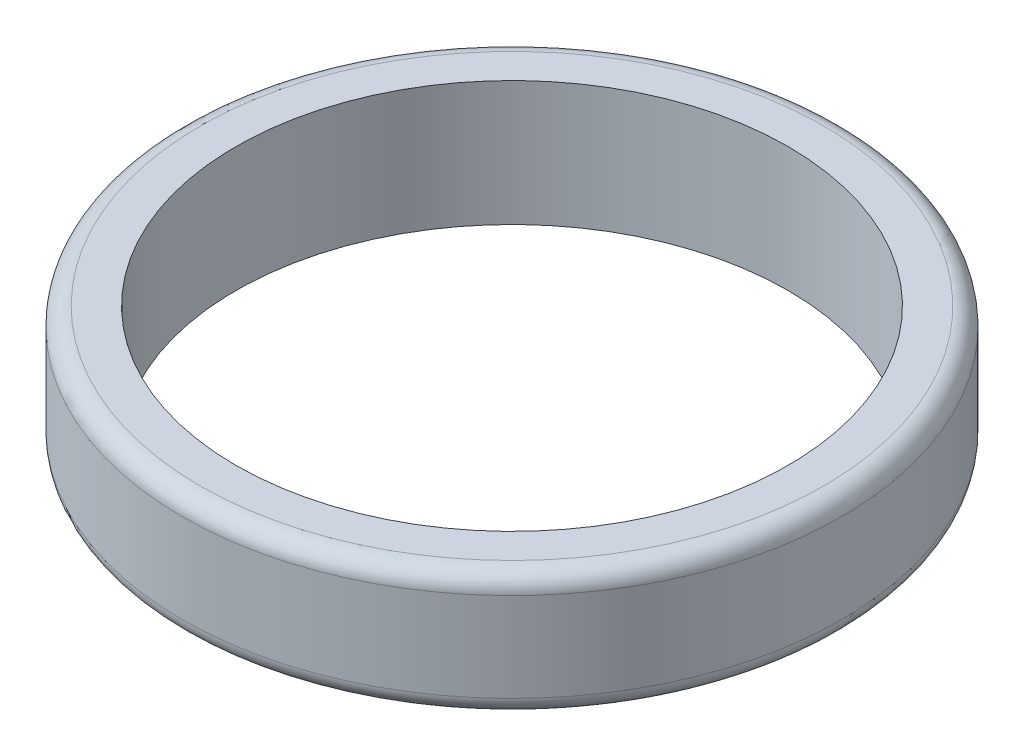
SolidWorks part; units mm, degrees
ref_plane "Front Plane" through (0, 0, 0) normal (0, 0, 1) x (1, 0, 0)
ref_plane "Top Plane" through (0, 0, 0) normal (0, 1, 0) x (1, 0, 0)
ref_plane "Right Plane" through (0, 0, 0) normal (1, 0, 0) x (0, 0, -1)
sketch "Sketch1" plane through (0, 0, 0) normal (0, 1, 0) x (1, 0, 0)
  circle A0 centre (0, 0) radius 15.5
  circle A1 centre (0, 0) radius 18.5
  dimension "D1" = 37
  dimension "D2" = 31
extrude "Boss-Extrude1" add sketch "Sketch1" along normal blind 7
fillet "Fillet1" radius 1 2 edges at (0, 0, 18.5) (0, 7, 18.5)
